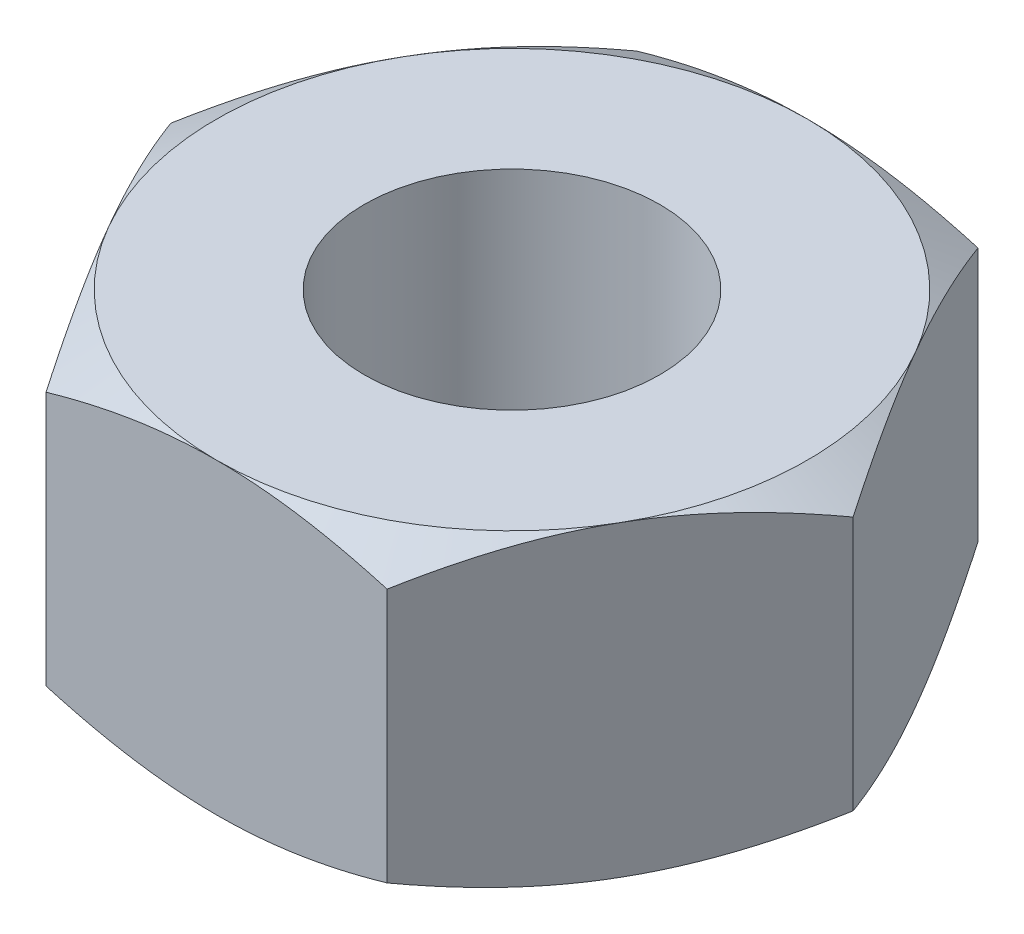
SolidWorks part; units mm, degrees
material "Plain Carbon Steel"
ref_plane "Front Plane" through (0, 0, 0) normal (0, 0, 1) x (1, 0, 0)
ref_plane "Top Plane" through (0, 0, 0) normal (0, 1, 0) x (1, 0, 0)
ref_plane "Right Plane" through (0, 0, 0) normal (1, 0, 0) x (0, 0, -1)
sketch "Sketch1" plane through (0, 0, 0) normal (0, 1, 0) x (1, 0, 0)
  line L1 (5.7735, 0) -> (2.8868, 5)
  line L2 (2.8868, 5) -> (-2.8868, 5)
  line L3 (-2.8868, 5) -> (-5.7735, 0)
  line L4 (-5.7735, 0) -> (-2.8868, -5)
  line L5 (-2.8868, -5) -> (2.8868, -5)
  line L6 (2.8868, -5) -> (5.7735, 0)
  circle A0 centre (0, 0) radius 5 construction
  circle A1 centre (0, 0) radius 2.5
  dimension "D1" = 5
  dimension "D2" = 10
extrude "Boss-Extrude1" add sketch "Sketch1" along normal mid plane 5.2
cosmetic thread "Cosmetic Thread1" parameters "D2"=6
sketch "Sketch3" plane through (0, 0, 0) normal (1, 0, 0) x (0, 0, -1)
  line L0 (4.134, 3.1) -> (5.866, 2.1)
  line L1 (5, 2.6) -> (5, -2.6) construction
  line L2 (5, 2.6) -> (6.3632, 4.9612) construction
  line L3 (4.134, 3.1) -> (4.634, 3.966)
  line L4 (4.634, 3.966) -> (6.366, 2.966)
  line L5 (6.366, 2.966) -> (5.866, 2.1)
  line L6 (0, -2.6) -> (0, 2.6) construction
  dimension "D1" = 60
  dimension "D2" = 2
  dimension "D3" = 1
revolve "Cut-Revolve2" cut sketch "Sketch3" angle 360 about L6
mirror "Mirror1" about plane through (0, 0, 0) normal (0, 1, 0) of "Cut-Revolve2"
